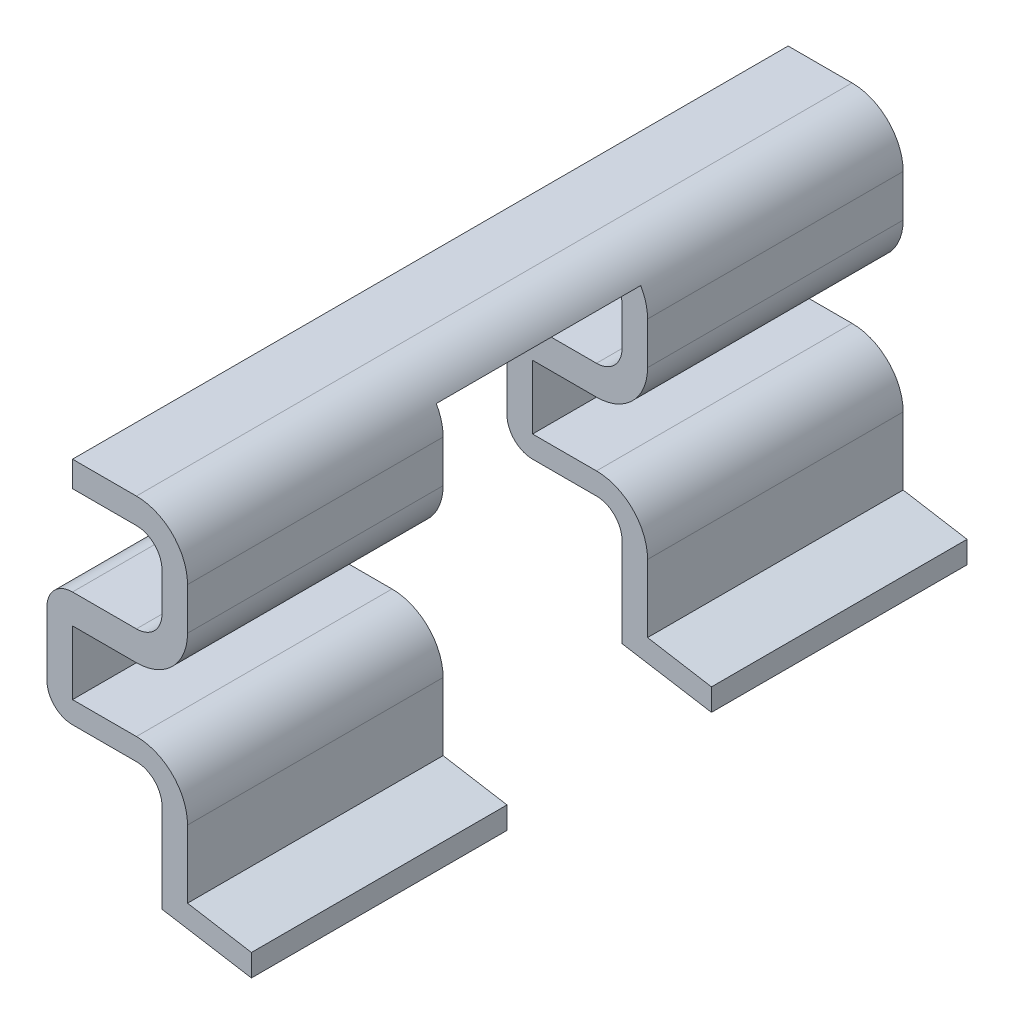
SolidWorks part; units mm, degrees
ref_plane "Front Plane" through (0, 0, 0) normal (0, 0, 1) x (1, 0, 0)
ref_plane "Top Plane" through (0, 0, 0) normal (0, 1, 0) x (1, 0, 0)
ref_plane "Right Plane" through (0, 0, 0) normal (1, 0, 0) x (0, 0, -1)
sketch "Sketch1" plane through (0, 0, 0) normal (0, 0, 1) x (1, 0, 0)
  line L0 (-0.2046, 39.9892) -> (-0.2046, -43.0196) construction
  line L1 (-50.3702, -11.5) -> (-50.3702, -6.5)
  line L2 (-50.3702, -6.5) -> (-50.3702, -13.5)
  line L3 (-52.3702, -4.5) -> (-57.3702, -4.5)
  line L4 (-52.3702, 4.5) -> (-57.3702, 4.5)
  line L5 (-59.3702, -2.5) -> (-59.3702, 2.5)
  line L6 (-50.3702, 6.5) -> (-50.3702, 9.5)
  line L7 (-50.3702, 19.7118) -> (54.6448, 19.7118) construction
  line L8 (-22.7917, 17.8004) -> (22.3825, 17.8004) construction
  line L9 (-48.9295, 13.8589) -> (-25.9631, 17.5474) construction
  line L10 (48.5203, 13.8589) -> (25.5539, 17.5474) construction
  line L11 (50.2032, 6.5) -> (50.2032, 11.8842) construction
  line L12 (59.3702, -2.5) -> (59.3702, 2.5) construction
  line L13 (52.2032, 4.5) -> (57.3702, 4.5) construction
  line L14 (52.2032, -4.5) -> (57.3702, -4.5) construction
  line L15 (50.2032, -6.5) -> (50.2032, -13.5886) construction
  line L16 (-50.3702, 6.5) -> (-50.3702, 9.5)
  line L17 (-59.3702, 0) -> (59.3702, 0) construction
  line L18 (50.2032, -13.5886) -> (25.5539, -17.5474) construction
  line L19 (-50.3702, -13.5) -> (-43.3702, -14.6608)
  line L20 (-22.7917, -17.8004) -> (22.3825, -17.8004) construction
  line L21 (-48.3702, -6.7956) -> (-48.3702, -12.0912)
  line L22 (-48.3702, -12.0912) -> (-43.3702, -12.9307)
  line L23 (-22.7843, -16.1121) -> (22.314, -16.3417) construction
  line L24 (48.1543, -12.557) -> (25.1694, -16.1285) construction
  line L25 (48.1813, -7.2615) -> (48.1543, -12.557) construction
  line L26 (52.2016, -3.2819) -> (57.2015, -3.3073) construction
  line L27 (57.2015, -3.3073) -> (57.2299, 2.2804) construction
  line L28 (52.1656, 2.2804) -> (57.2299, 2.2804) construction
  line L29 (48.1656, 6.2804) -> (48.1656, 11.5759) construction
  line L30 (48.1656, 11.5759) -> (25.1991, 15.2644) construction
  line L31 (-22.7541, 15.4921) -> (22.3449, 15.4921) construction
  line L32 (-48.5748, 11.5759) -> (-25.6083, 15.2644) construction
  line L33 (-48.3702, 6.2044) -> (-48.3702, 9.5)
  line L34 (-52.3702, 2.2044) -> (-57.3702, 2.2044)
  line L35 (-57.3702, -2.7956) -> (-57.3702, 2.2044)
  line L36 (-52.3702, -2.7956) -> (-57.3702, -2.7956)
  line L38 (-52.3702, 11.5) -> (-57.3702, 11.5)
  line L39 (-52.3702, 13.5) -> (-57.3702, 13.5)
  line L40 (-50.3702, 19.7118) -> (-50.3702, 37)
  line L41 (-57.3702, 13.5) -> (-57.3702, 11.5)
  line L42 (-43.3702, -12.9307) -> (-43.3702, -16.0073)
  line L43 (-32.4017, -16.4797) -> (-25.9631, -17.5474)
  line L44 (-32.6973, -14.6992) -> (-25.6374, -15.8699)
  circle A0 centre (-0.2046, -10.2196) radius 32.8 construction
  circle A1 centre (-71.8897, -10.2196) radius 5.115 construction
  arc A2 (25.5539, 17.5474) -> (22.3825, 17.8004) centre (22.3825, -2.1996) ccw construction
  arc A3 (-25.9631, 17.5474) -> (-22.7917, 17.8004) centre (-22.7917, -2.1996) cw construction
  arc A4 (59.3702, 2.5) -> (57.3702, 4.5) centre (57.3702, 2.5) ccw construction
  arc A5 (59.3702, -2.5) -> (57.3702, -4.5) centre (57.3702, -2.5) cw construction
  arc A6 (50.2032, -6.5) -> (52.2032, -4.5) centre (52.2032, -6.5) cw construction
  arc A7 (50.2032, 6.5) -> (52.2032, 4.5) centre (52.2032, 6.5) ccw construction
  arc A8 (48.5203, 13.8589) -> (50.2032, 11.8842) centre (48.2032, 11.8842) cw construction
  arc A10 (-52.3702, -4.5) -> (-50.3702, -6.5) centre (-52.3702, -6.5) cw
  arc A11 (-50.3702, 6.5) -> (-52.3702, 4.5) centre (-52.3702, 6.5) cw
  arc A12 (-57.3702, 4.5) -> (-59.3702, 2.5) centre (-57.3702, 2.5) ccw
  arc A13 (-57.3702, -4.5) -> (-59.3702, -2.5) centre (-57.3702, -2.5) cw
  arc A14 (25.5539, -17.5474) -> (22.3825, -17.8004) centre (22.3825, 2.1996) cw construction
  arc A15 (-25.9631, -17.5474) -> (-22.7917, -17.8004) centre (-22.7917, 2.1996) ccw construction
  arc A16 (-25.6374, -15.8699) -> (-22.7843, -16.1121) centre (-22.6927, 1.8876) ccw construction
  arc A17 (25.1694, -16.1285) -> (22.314, -16.3417) centre (22.4056, 1.6581) cw construction
  arc A18 (48.1813, -7.2615) -> (52.2016, -3.2819) centre (52.1812, -7.2818) cw construction
  arc A19 (48.1656, 6.2804) -> (52.1656, 2.2804) centre (52.1656, 6.2804) ccw construction
  arc A20 (25.1991, 15.2644) -> (22.3449, 15.4921) centre (22.3449, -2.5079) ccw construction
  arc A21 (-25.6083, 15.2644) -> (-22.7541, 15.4921) centre (-22.7541, -2.5079) cw construction
  arc A22 (-48.3702, 6.2044) -> (-52.3702, 2.2044) centre (-52.3702, 6.2044) cw
  arc A23 (-52.3702, -2.7956) -> (-48.3702, -6.7956) centre (-52.3702, -6.7956) cw
  arc A24 (-52.3702, 13.5) -> (-48.3702, 9.5) centre (-52.3702, 9.5) cw
  arc A25 (-52.3702, 11.5) -> (-50.3702, 9.5) centre (-52.3702, 9.5) cw
  point P19 (-0.2046, 17.8004)
  dimension "D1" = 65.6
  dimension "D2" = 20
  dimension "D3" = 2
  dimension "D4" = 5
  dimension "D5" = 3
  dimension "D6" = 5
sketch "Sketch2" plane through (0, 0, 0) normal (0, 0, 1) x (1, 0, 0)
  line L0 (-52.3702, 11.5) -> (-57.3702, 11.5) construction
  line L1 (-57.3702, 13.5) -> (-57.3702, 11.5) construction
  line L2 (-52.3702, 13.5) -> (-57.3702, 13.5) construction
  line L3 (-48.3702, 6.2044) -> (-48.3702, 9.5) construction
  line L4 (-52.3702, 2.2044) -> (-57.3702, 2.2044) construction
  line L5 (-57.3702, -2.7956) -> (-57.3702, 2.2044) construction
  line L6 (-52.3702, -2.7956) -> (-57.3702, -2.7956) construction
  line L7 (-48.3702, -6.7956) -> (-48.3702, -12.0912) construction
  line L8 (-48.3702, -12.0912) -> (-43.3702, -12.9307) construction
  line L9 (-43.3702, -12.9307) -> (-43.3702, -16.0073) construction
  line L11 (-50.3702, -6.5) -> (-50.3702, -13.5) construction
  line L12 (-50.3702, -13.5) -> (-43.3702, -14.6608) construction
  line L13 (-50.3702, -11.5) -> (-50.3702, -6.5) construction
  line L15 (-50.3702, 6.5) -> (-50.3702, 9.5) construction
  line L16 (-50.3702, 6.5) -> (-50.3702, 9.5) construction
  line L17 (-52.3702, -4.5) -> (-57.3702, -4.5) construction
  line L18 (-59.3702, -2.5) -> (-59.3702, 2.5) construction
  line L19 (-52.3702, 4.5) -> (-57.3702, 4.5) construction
  line L21 (-52.3702, 11.5) -> (-57.3702, 11.5)
  line L22 (-57.3702, 13.5) -> (-57.3702, 11.5)
  line L23 (-52.3702, 13.5) -> (-57.3702, 13.5)
  line L24 (-48.3702, 6.2044) -> (-48.3702, 9.5)
  line L25 (-52.3702, 2.2044) -> (-57.3702, 2.2044)
  line L26 (-57.3702, -2.7956) -> (-57.3702, 2.2044)
  line L27 (-52.3702, -2.7956) -> (-57.3702, -2.7956)
  line L28 (-48.3702, -6.7956) -> (-48.3702, -12.0912)
  line L29 (-48.3702, -12.0912) -> (-43.3702, -12.9307)
  line L30 (-43.3702, -12.9307) -> (-43.3702, -14.6608)
  line L32 (-50.3702, -6.5) -> (-50.3702, -13.5)
  line L33 (-50.3702, -13.5) -> (-43.3702, -14.6608)
  line L34 (-50.3702, -11.5) -> (-50.3702, -6.5)
  line L36 (-50.3702, 6.5) -> (-50.3702, 9.5)
  line L37 (-50.3702, 6.5) -> (-50.3702, 9.5)
  line L38 (-52.3702, -4.5) -> (-57.3702, -4.5)
  line L39 (-59.3702, -2.5) -> (-59.3702, 2.5)
  line L40 (-52.3702, 4.5) -> (-57.3702, 4.5)
  arc A0 (-50.3702, 9.5) -> (-52.3702, 11.5) centre (-52.3702, 9.5) ccw construction
  arc A1 (-48.3702, 9.5) -> (-52.3702, 13.5) centre (-52.3702, 9.5) ccw construction
  arc A2 (-52.3702, 2.2044) -> (-48.3702, 6.2044) centre (-52.3702, 6.2044) ccw construction
  arc A3 (-48.3702, -6.7956) -> (-52.3702, -2.7956) centre (-52.3702, -6.7956) ccw construction
  arc A4 (-50.3702, -6.5) -> (-52.3702, -4.5) centre (-52.3702, -6.5) ccw construction
  arc A5 (-59.3702, -2.5) -> (-57.3702, -4.5) centre (-57.3702, -2.5) ccw construction
  arc A6 (-57.3702, 4.5) -> (-59.3702, 2.5) centre (-57.3702, 2.5) ccw construction
  arc A7 (-52.3702, 4.5) -> (-50.3702, 6.5) centre (-52.3702, 6.5) ccw construction
  arc A8 (-50.3702, 9.5) -> (-52.3702, 11.5) centre (-52.3702, 9.5) ccw
  arc A9 (-48.3702, 9.5) -> (-52.3702, 13.5) centre (-52.3702, 9.5) ccw
  arc A10 (-52.3702, 2.2044) -> (-48.3702, 6.2044) centre (-52.3702, 6.2044) ccw
  arc A11 (-48.3702, -6.7956) -> (-52.3702, -2.7956) centre (-52.3702, -6.7956) ccw
  arc A12 (-50.3702, -6.5) -> (-52.3702, -4.5) centre (-52.3702, -6.5) ccw
  arc A13 (-59.3702, -2.5) -> (-57.3702, -4.5) centre (-57.3702, -2.5) ccw
  arc A14 (-57.3702, 4.5) -> (-59.3702, 2.5) centre (-57.3702, 2.5) ccw
  arc A15 (-52.3702, 4.5) -> (-50.3702, 6.5) centre (-52.3702, 6.5) ccw
extrude "Boss-Extrude1" add sketch "Sketch2" along normal blind 56 contours A15 L40 A14 L39 A13 L38 A12 L32 L33 L30 L29 L28 A11 L27 L26 L25 A10 L24 A9 L23 L22 L21 A8 L36
sketch "Sketch3" plane through (-59.3702, 0, 0) normal (-1, 0, 0) x (0, 0, 1)
  line L0 (56, -2.5) -> (0, -2.5) construction
  line L1 (56, -2.5) -> (0, -2.5) construction
  line L3 (28, -30.6109) -> (28, 24.7018) construction
  line L4 (36, -16.5) -> (20, -16.5)
  line L5 (36, -16.5) -> (36, 11.5)
  line L6 (36, 11.5) -> (20, 11.5)
  line L7 (20, -16.5) -> (20, 11.5)
  line L8 (36, -16.5) -> (20, 11.5) construction
  line L9 (36, 11.5) -> (20, -16.5) construction
  line L10 (56, 11.5) -> (0, 11.5) construction
  point P2 (28, -2.5)
  point P3 (28, -2.5)
  dimension "D1" = 16
extrude "Cut-Extrude1" cut sketch "Sketch3" against normal through all
